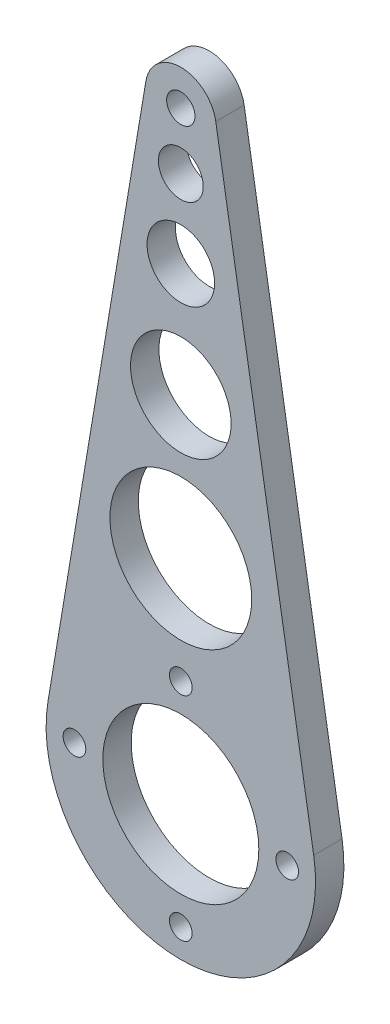
SolidWorks part; units mm, degrees
ref_plane "Plan de face" through (0, 0, 0) normal (0, 0, 1) x (1, 0, 0)
ref_plane "Plan de dessus" through (0, 0, 0) normal (0, 1, 0) x (1, 0, 0)
ref_plane "Plan de droite" through (0, 0, 0) normal (1, 0, 0) x (0, 0, -1)
sketch "Esquisse1" plane through (0, 0, 0) normal (0, 0, 1) x (1, 0, 0)
  line L0 (0, 0) -> (0, 85) construction
  line L1 (-18.7405, 3.1294) -> (-4.9317, 85.8235)
  line L2 (18.7405, 3.1294) -> (4.9317, 85.8235)
  line L3 (-1.9787, 85.2909) -> (-9.8936, 31.4545) construction
  circle A0 centre (0, 0) radius 15 construction
  circle A1 centre (0, 15) radius 1.6
  circle A2 centre (15, 0) radius 1.6
  circle A3 centre (0, -15) radius 1.6
  circle A4 centre (-15, 0) radius 1.6
  circle A5 centre (0, 0) radius 11
  arc A6 (-18.7405, 3.1294) -> (18.7405, 3.1294) centre (0, 0) ccw
  arc A7 (4.9317, 85.8235) -> (-4.9317, 85.8235) centre (0, 85) ccw
  circle A8 centre (0, 85) radius 2
  circle A9 centre (0, 77) radius 3.1636
  circle A10 centre (0, 30) radius 10
  circle A11 centre (0, 50) radius 7.0909
  circle A12 centre (0, 66) radius 4.7636
  point P14 (0, 0)
  point P29 (0, 0)
  dimension "D1" = 30
  dimension "D2" = 3.2
  dimension "D4" = 22
  dimension "D5" = 38
  dimension "D6" = 10
  dimension "D8" = 4
  dimension "D9" = 11
  dimension "D11" = 20
  dimension "D7" = 85
  dimension "D10" = 30
  dimension "D12" = 20
  dimension "D13" = 16
  dimension "D3" = 4
extrude "Boss.-Extru.1" add sketch "Esquisse1" along normal blind 4
